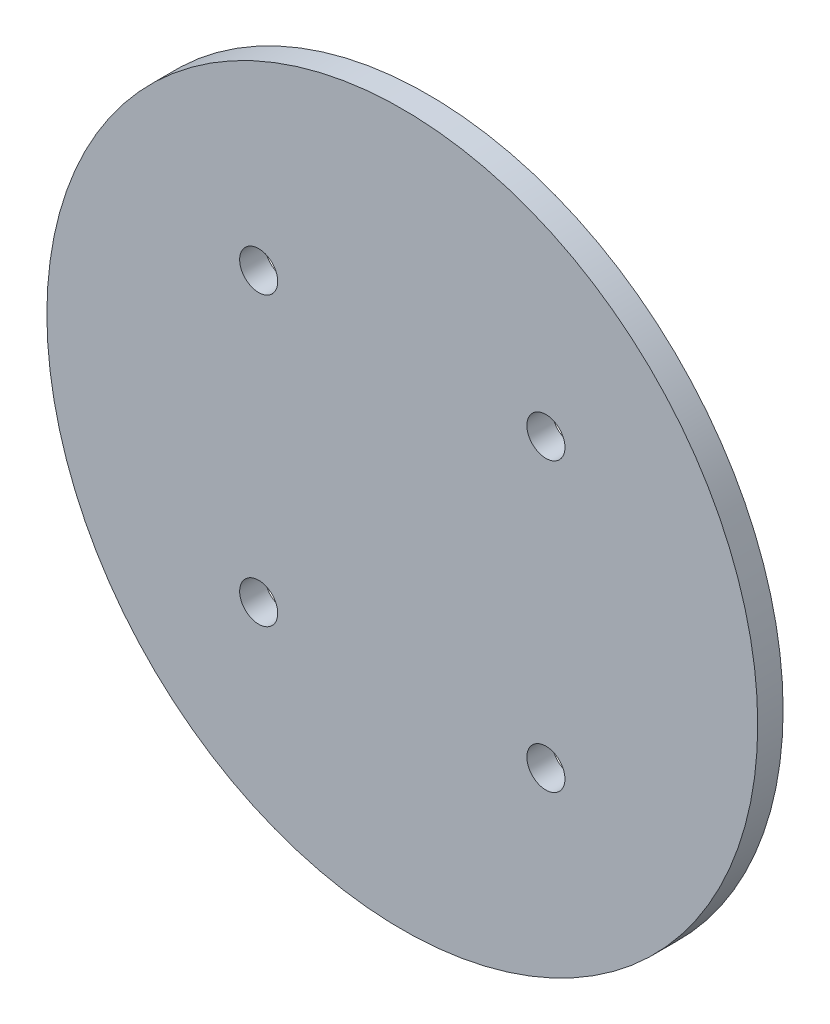
SolidWorks part; units mm, degrees
ref_plane "Front Plane" through (0, 0, 0) normal (0, 0, 1) x (1, 0, 0)
ref_plane "Top Plane" through (0, 0, 0) normal (0, 1, 0) x (1, 0, 0)
ref_plane "Right Plane" through (0, 0, 0) normal (1, 0, 0) x (0, 0, -1)
sketch "Sketch1" plane through (0, 0, 0) normal (0, 0, 1) x (1, 0, 0)
  circle A0 centre (0, 0) radius 88.9
  dimension "D1" = 177.8
extrude "Boss-Extrude1" add sketch "Sketch1" along normal blind 6.35
sketch "Sketch2" plane through (0, 0, 6.35) normal (0, 0, 1) x (1, 0, 0)
  line L0 (0, 88.9) -> (0, -88.9) construction
  line L1 (-88.9, 0) -> (88.9, 0) construction
  line L2 (-35.921, 35.921) -> (0, 0) construction
  circle A0 centre (0, 0) radius 88.9 construction
  circle A1 centre (-35.921, 35.921) radius 4.7625
  circle A2 centre (35.921, 35.921) radius 4.7625
  circle A3 centre (35.921, -35.921) radius 4.7625
  circle A4 centre (-35.921, -35.921) radius 4.7625
  dimension "D3" = 9.525
  dimension "D1" = 45
  dimension "D2" = 50.8
extrude "Cut-Extrude1" cut sketch "Sketch2" against normal through all both and the other way through all
equation "\"Wheel Thickness\"= 1in"
equation "\"Wheel Diameter\"= 3in"
equation "\"Motor Rear Diameter\" = 36.2mm"
equation "\"Motor Front Diameter\" = 12mm"
equation "\"Material Thickness\" = .25in"
equation "\"Wheel Cutout Diameter\"= 2cm"
equation "\"Motor Mount Tab Thickness\" = 100mm"
equation "\"Motor Mount Tab Height\" = 40mm"
equation "\"Motor Shaft Diameter\" = 3mm"
equation "\"Wheel Radius Clearance\" = 5mm"
equation "\"Wheel Cutout Width\" = 1.5in"
equation "\"Base Diameter\" = 10in"
equation "\"Wheel Mount Distance\" = 5mm"
equation "\"Motor Mount Distance\" = 50mm"
equation "\"Motor Cutout Length\" = 6in"
equation "\"Motor Cutout Height\" = 2in "
equation "\"Rod Diameter\" = 3/8in"
equation "\"Rod Length\" = 1in"
equation "\"Barrel Front Length\" = 1.8in"
equation "\"Barrerl Rear Length\" = 5in "
equation "\"Barrel Fillet Radius\" = 1in "
equation "\"Barrel Angle\" = 25deg"
equation "\"Barrel Diameter\" = 50mm"
equation "\"Barrel Shell Width\" = 2mm"
equation "\"Second Level Diameter\" = 10in"
equation "\"Ball Diameter\" = 40mm"
equation "\"Third Level Length\" = 9in"
equation "\"Third Level Height\" = 9in"
equation "\"Barrel Tab Clearance\" = 5mm"
equation "\"Barrel Tab Distance Away\" = 2mm"
equation "\"Hole Distance Apart\" = 2.8in"
equation "\"Barrel Tab Distance\"= 1.5in "
equation "\"Third Level Rod Distance\" = .5in"
equation " \"Second Rod Diameter\" = 3/8in"
equation "\"Second Rod Length\" = 3.88in"
equation "\"Bumper Wheel Clearance\" = 1.2in"
equation "\"Servo Tab Height\" = 4in"
equation "\"Servo Tab Width\" = 2in"
equation "\"Servo Tab Hole Horizontal Distance\" = 1in"
equation "\"Servo Tab Hole Vertical Distance\" = 1.5in "
equation "\"Servo Hole Vertical Distance\" = 3in"
equation "\"Servo Hole Diameter\" = 1/4in"
equation "\"Servo Hole Shaft Length\" = 1.45in"
equation "\"Third Rod Length\" = 5in"
equation "\"Third Rod Diameter\" = 3/8in"
equation "\"Third Rod Radius Distance\" = 2in"
equation "\"Third Rod Angle Distance\" = 45deg"
equation "\"Fourth Level Diameter\" = 7in"
equation "\"D1@Sketch1\"=\"Fourth Level Diameter\""
equation "\"D1@Boss-Extrude1\"=\"Material Thickness\""
equation "\"D3@Sketch2\"=\"Third Rod Diameter\""
equation "\"D1@Sketch2\"=\"Third Rod Angle Distance\""
equation "\"D2@Sketch2\"=\"Third Rod Radius Distance\""
